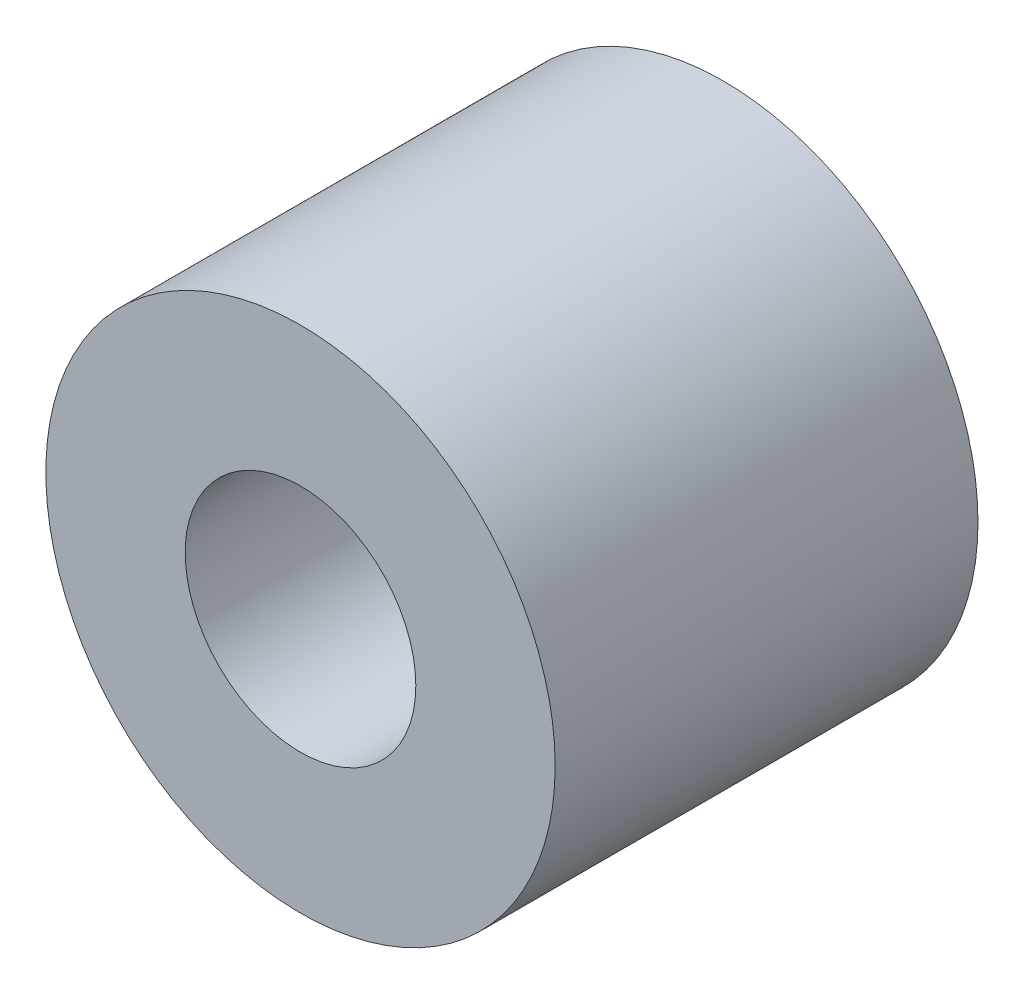
SolidWorks part; units mm, degrees
material "Polyester Resin"
ref_plane "Front Plane" through (0, 0, 0) normal (0, 0, 1) x (1, 0, 0)
ref_plane "Top Plane" through (0, 0, 0) normal (0, 1, 0) x (1, 0, 0)
ref_plane "Right Plane" through (0, 0, 0) normal (1, 0, 0) x (0, 0, -1)
sketch "Sketch1" plane through (0, 0, 0) normal (0, 0, 1) x (1, 0, 0)
  circle A0 centre (0, 0) radius 26.5
  dimension "D1" = 53
extrude "Boss-Extrude1" add sketch "Sketch1" along normal blind 44
sketch "Sketch2" plane through (0, 0, 44) normal (0, 0, 1) x (1, 0, 0)
  circle A0 centre (0, 0) radius 12
  dimension "D1" = 24
extrude "Cut-Extrude1" cut sketch "Sketch2" against normal through all
